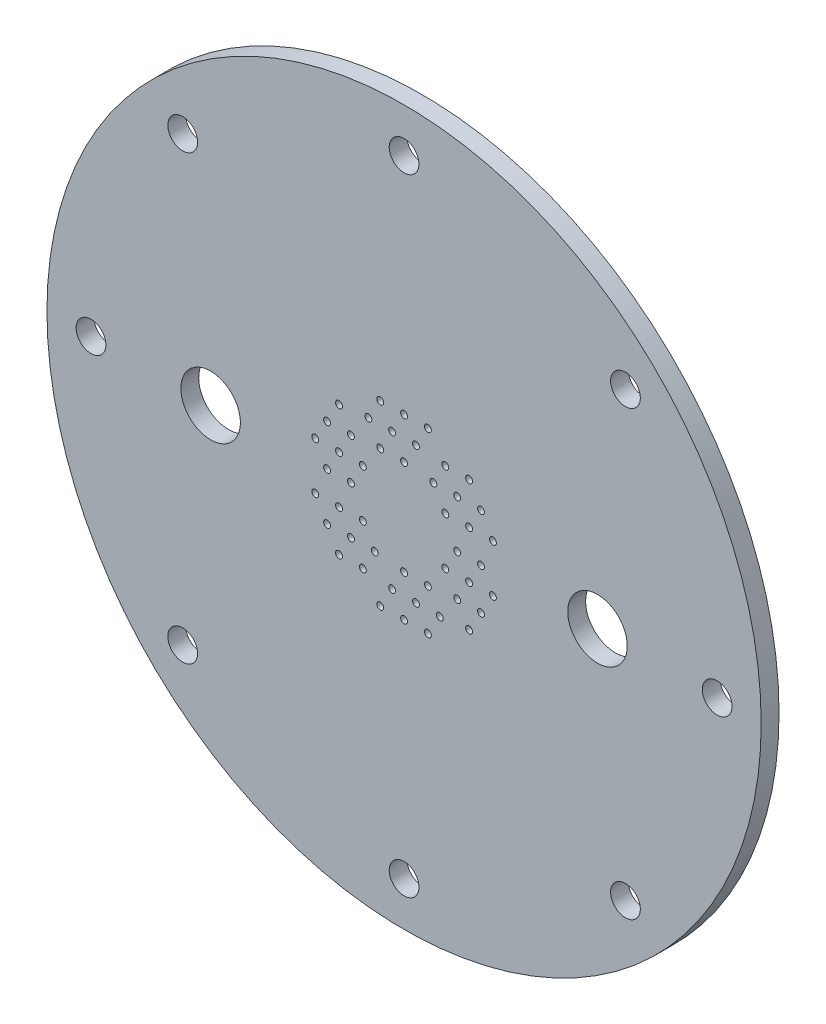
SolidWorks part; units mm, degrees
ref_plane "Front Plane" through (0, 0, 0) normal (0, 0, 1) x (1, 0, 0)
ref_plane "Top Plane" through (0, 0, 0) normal (0, 1, 0) x (1, 0, 0)
ref_plane "Right Plane" through (0, 0, 0) normal (1, 0, 0) x (0, 0, -1)
sketch "Sketch1" plane through (0, 0, 0) normal (0, 0, 1) x (1, 0, 0)
  circle A0 centre (0, 0) radius 76.2
  dimension "Top Injector Diameter" = 152.4
extrude "Boss-Extrude1" add sketch "Sketch1" along normal blind 3.81
sketch "Sketch2" plane through (0, 0, 0) normal (0, 0, -1) x (-1, 0, 0)
  line L0 (0, 0) -> (0, 10.16) construction
  line L1 (0, 10.16) -> (5.08, 10.16) construction
  line L2 (5.08, 10.16) -> (7.62, 14.5594) construction
  line L3 (7.62, 14.5594) -> (2.54, 14.5594) construction
  line L4 (2.54, 14.5594) -> (5.08, 10.16) construction
  line L5 (0, 10.16) -> (2.54, 14.5594) construction
  line L6 (0, 10.16) -> (-2.54, 14.5594) construction
  line L7 (-2.54, 14.5594) -> (2.54, 14.5594) construction
  line L8 (2.54, 14.5594) -> (5.08, 18.9588) construction
  line L9 (5.08, 18.9588) -> (7.62, 14.5594) construction
  line L10 (-2.54, 14.5594) -> (-5.08, 18.9588) construction
  line L11 (-5.08, 18.9588) -> (0, 18.9588) construction
  line L12 (0, 18.9588) -> (-2.54, 14.5594) construction
  line L13 (0, 18.9588) -> (2.54, 14.5594) construction
  line L14 (0, 18.9588) -> (5.08, 18.9588) construction
  circle A0 centre (0, 10.16) radius 0.7366
  circle A1 centre (2.54, 14.5594) radius 0.7366
  circle A2 centre (5.08, 10.16) radius 0.7366
  circle A3 centre (7.62, 14.5594) radius 0.7366
  circle A4 centre (-2.54, 14.5594) radius 0.7366
  circle A5 centre (-5.08, 18.9588) radius 0.7366
  circle A6 centre (0, 18.9588) radius 0.7366
  circle A7 centre (5.08, 18.9588) radius 0.7366
  dimension "Top Injector Hole Diameter" = 1.4732
  dimension "Distance Between Holes" = 5.08
  dimension "Top Injector Hole Distance from Center" = 10.16
extrude "Cut-Extrude1" cut sketch "Sketch2" against normal through all
pattern_circular "CirPattern1" count 6 over 360 about axis through (0, 0, 0) along (0, 0, 1) of "Cut-Extrude1"
sketch "Sketch3" plane through (0, 0, 0) normal (0, 0, -1) x (-1, 0, 0)
  line L0 (-41.275, 0) -> (41.275, 0) construction
  circle A0 centre (41.275, 0) radius 6.35
  circle A1 centre (-41.275, 0) radius 6.35
  point P4 (0, 0)
  dimension "Top Injector Valves Diameter" = 12.7
  dimension "Top Injector Manifold Valves" = 82.55
extrude "Cut-Extrude2" cut sketch "Sketch3" against normal through all
sketch "Sketch5" plane through (0, 0, 0) normal (0, 0, -1) x (-1, 0, 0)
  line L0 (0, 0) -> (66.802, 0) construction
  circle A0 centre (66.802, 0) radius 3.175
  dimension "Top Injector Hole Diameter" = 6.35
  dimension "Top Injector Screw Holes Distance" = 66.802
extrude "Cut-Extrude3" cut sketch "Sketch5" against normal through all
pattern_circular "CirPattern2" count 8 over 360 about axis through (0, 0, 0) along (0, 0, 1) of "Cut-Extrude3"
sketch "Sketch6" plane through (0, 0, 0) normal (1, 0, 0) x (0, 0, -1)
  line L0 (0, -76.2) -> (0, 76.2) construction
  line L1 (0, 53.34) -> (1.27, 53.34)
  line L2 (0, 53.34) -> (0, 50.8)
  line L3 (0, 50.8) -> (1.27, 50.8)
  line L4 (1.27, 53.34) -> (1.27, 50.8)
  line L5 (0, 76.2) -> (-3.81, 76.2) construction
  line L6 (0, 0) -> (-3.81, 0) construction
  line L7 (-3.81, 76.2) -> (-3.81, -76.2) construction
  dimension "Locator Ring Width" = 2.54
  dimension "Locator Ring Distance From Edge" = 25.4
  dimension "Locator Ring Depth" = 1.27
revolve "Revolve1" add sketch "Sketch6" angle 360 about L6
equation "\"Top Injector Diameter\"=6"
equation "\"Top Injector Height\"=0.15"
equation "\"Distance Between Holes\"=0.2"
equation "\"Top Injector Hole Distance from Center\"=0.4"
equation "\"Top Injector Hole Diameter\"=0.058"
equation "\"Top Injector Manifold Valves\"=3.25"
equation "\"Top Injector Valves Diameter\"=0.5"
equation "\"Top Injector Screw Holes Distance\"=2.63"
equation "\"Top Injector Screw Hole Diameter\"=0.25"
